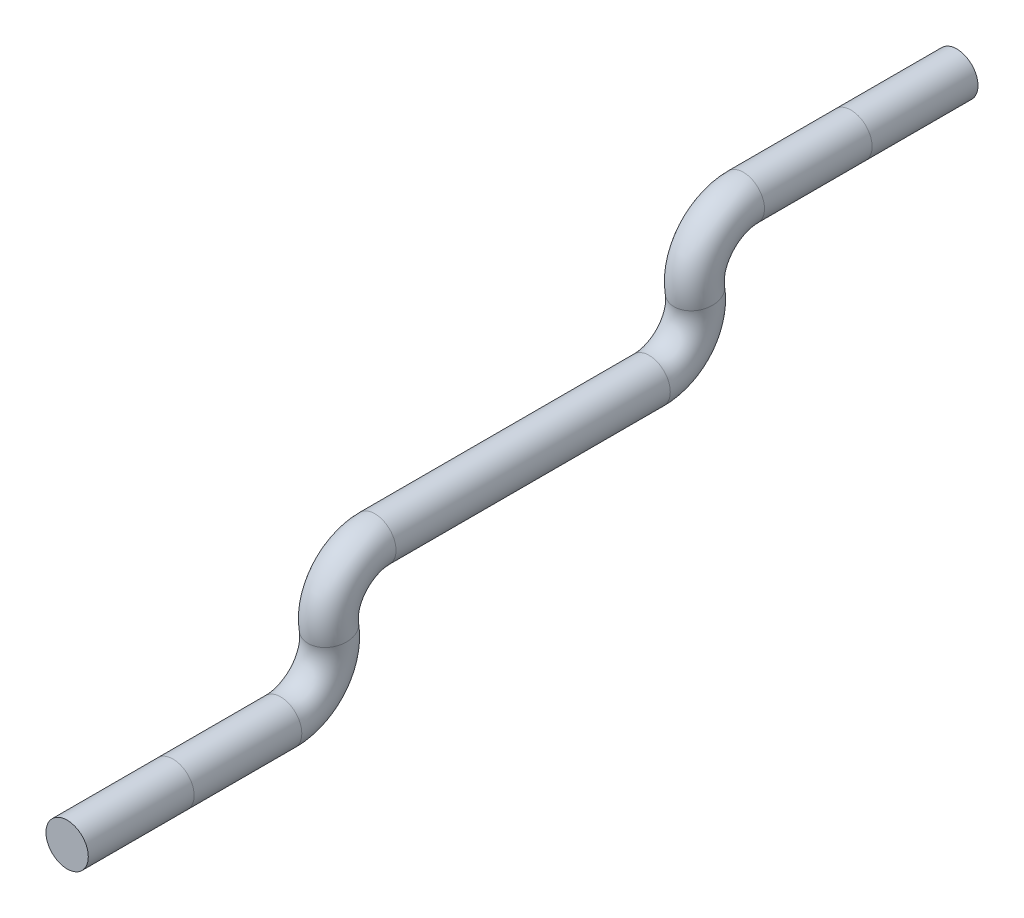
SolidWorks part; units mm, degrees
ref_plane "Front Plane" through (0, 0, 0) normal (0, 0, 1) x (1, 0, 0)
ref_plane "Top Plane" through (0, 0, 0) normal (0, 1, 0) x (1, 0, 0)
ref_plane "Right Plane" through (0, 0, 0) normal (1, 0, 0) x (0, 0, -1)
sketch "Sketch1" plane through (0, 0, 0) normal (1, 0, 0) x (0, 0, -1)
  line L0 (-64.7763, 0) -> (64.7763, 0)
  line L1 (109.2742, 52.6742) -> (160.1248, 52.6742)
  line L2 (-160.1248, -52.6742) -> (-210.1248, -52.6742)
  line L3 (160.1248, 52.6742) -> (210.1248, 52.6742)
  line L5 (-109.2742, -52.6742) -> (-160.1248, -52.6742)
  arc A0 (64.7763, 0) -> (86.4408, 25.6452) centre (64.7763, 21.9734) ccw
  arc A1 (86.4408, 25.6452) -> (109.2742, 52.6742) centre (109.2742, 29.5151) cw
  arc A4 (-64.7763, 0) -> (-86.4408, -25.6452) centre (-64.7763, -21.9734) ccw
  arc A5 (-86.4408, -25.6452) -> (-109.2742, -52.6742) centre (-109.2742, -29.5151) cw
ref_plane "Plane2" through (0, -52.6742, 210.1248) normal (0, 0, 1) x (1, 0, 0)
sketch "Sketch3" plane through (0, -52.6742, 210.1248) normal (0, 0, 1) x (1, 0, 0)
  line L0 (0, 0) -> (0, 27.029) construction
  circle A0 centre (0, 0) radius 10
  dimension "D1" = 20
sweep "Sweep2" add profiles "Sketch3" path "Sketch1"
